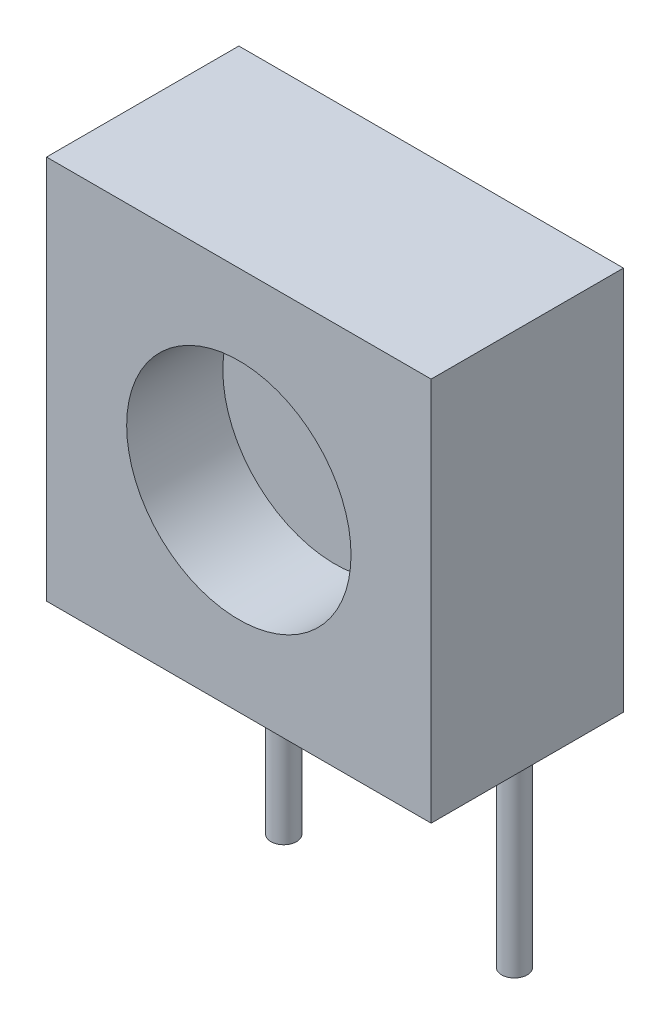
SolidWorks part; units mm, degrees
ref_plane "Front" through (0, 0, 0) normal (0, 0, 1) x (1, 0, 0)
ref_plane "Top" through (0, 0, 0) normal (0, 1, 0) x (1, 0, 0)
ref_plane "Right" through (0, 0, 0) normal (1, 0, 0) x (0, 0, -1)
sketch "Sketch1" plane through (0, 0, 0) normal (0, 0, 1) x (1, 0, 0)
  line L0 (0, 0) -> (6, 6) construction
  line L1 (0, 0) -> (6, 0)
  line L2 (0, 0) -> (0, 6)
  line L3 (0, 6) -> (6, 6)
  line L4 (6, 0) -> (6, 6)
  line L5 (6, 0) -> (0, 6) construction
  circle A0 centre (3, 3) radius 1.75
  dimension "D3" = 3.5
  dimension "D1" = 6
  dimension "D2" = 6
extrude "Boss-Extrude1" add sketch "Sketch1" along normal blind 3
sketch "Sketch2" plane through (0, 0, 0) normal (0, 0, 1) x (1, 0, 0)
  line L1 (0, 6) -> (6, 6)
  line L2 (0, 6) -> (0, 0)
  line L3 (0, 0) -> (6, 0)
  line L4 (6, 6) -> (6, 0)
  point P5 (6, 0)
extrude "Boss-Extrude2" add sketch "Sketch2" along normal offset from surface (1.5 mm away) 1.5 up to face at (3, 3, 3)
sketch "Sketch3" plane through (0, 0, 0) normal (0, -1, 0) x (1, 0, 0)
  line L0 (-0.93, 0.5) -> (7.2787, 0.5) construction
  line L1 (0, 0) -> (6, 0) construction
  circle A0 centre (1.2, 0.5) radius 0.2
  circle A1 centre (4.8, 0.5) radius 0.2
  point P8 (3, 0)
  dimension "D2" = 0.4
  dimension "D3" = 0.4
  dimension "D1" = 0.5
  dimension "D4" = 3.6
  dimension "D5" = 1.8
extrude "Boss-Extrude3" add sketch "Sketch3" along normal blind 3.8
equation "\"D4@Sketch3\"=4-\"D2@Sketch3\""
equation "\"D5@Sketch3\"=\"D4@Sketch3\"/2"
